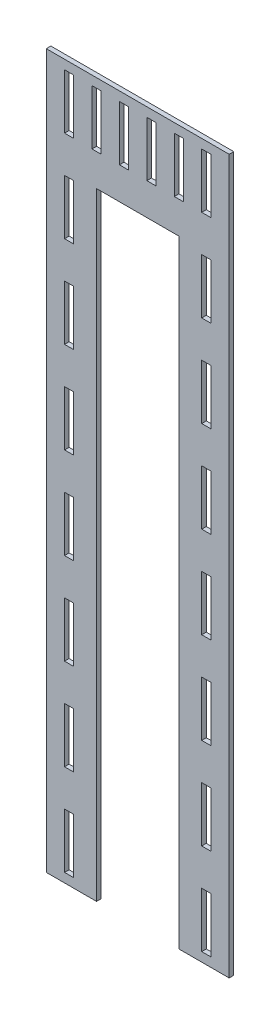
SolidWorks part; units mm, degrees
ref_plane "前视基准面" through (0, 0, 0) normal (0, 0, 1) x (1, 0, 0)
ref_plane "上视基准面" through (0, 0, 0) normal (0, 1, 0) x (1, 0, 0)
ref_plane "右视基准面" through (0, 0, 0) normal (1, 0, 0) x (0, 0, -1)
sketch "草图1" plane through (0, 0, 0) normal (0, 0, 1) x (1, 0, 0)
  line L0 (-4.5, 0) -> (-4.5, 67.5)
  line L1 (-10, 78) -> (10, 78)
  line L2 (-10, 78) -> (-10, 0)
  line L3 (-10, 0) -> (-4.5, 0)
  line L4 (10, 78) -> (10, 0)
  line L5 (-4.5, 67.5) -> (4.5, 67.5)
  line L6 (4.5, 67.5) -> (4.5, 0)
  line L7 (4.5, 0) -> (10, 0)
  dimension "D1" = 20
  dimension "D2" = 78
  dimension "D3" = 10
  dimension "D4" = 9
  dimension "D5" = 4.5
  dimension "D6" = 10.5
extrude "凸台-拉伸1" add sketch "草图1" along normal blind 0.5
sketch "草图3" plane through (0, 0, 0.5) normal (0, 0, 1) x (1, 0, 0)
  line L0 (-10, 78) -> (-10, 0) construction
  line L1 (-8, 77) -> (-7, 77)
  line L2 (-8, 77) -> (-8, 71)
  line L3 (-8, 71) -> (-7, 71)
  line L4 (-7, 77) -> (-7, 71)
  line L5 (10, 78) -> (-10, 78) construction
  line L6 (-5, 77) -> (-5, 71)
  line L7 (-5, 77) -> (-4, 77)
  line L8 (-4, 77) -> (-4, 71)
  line L9 (-5, 71) -> (-4, 71)
  line L10 (-2, 77) -> (-2, 71)
  line L11 (-2, 77) -> (-1, 77)
  line L12 (-1, 77) -> (-1, 71)
  line L13 (-2, 71) -> (-1, 71)
  line L14 (1, 77) -> (1, 71)
  line L15 (1, 77) -> (2, 77)
  line L16 (2, 77) -> (2, 71)
  line L17 (1, 71) -> (2, 71)
  line L18 (4, 77) -> (4, 71)
  line L19 (4, 77) -> (5, 77)
  line L20 (5, 77) -> (5, 71)
  line L21 (4, 71) -> (5, 71)
  line L22 (7, 77) -> (7, 71)
  line L23 (7, 77) -> (8, 77)
  line L24 (8, 77) -> (8, 71)
  line L25 (7, 71) -> (8, 71)
  line L26 (-8, 67) -> (-8, 61)
  line L27 (-8, 67) -> (-7, 67)
  line L28 (-7, 67) -> (-7, 61)
  line L29 (-8, 61) -> (-7, 61)
  line L30 (7, 67) -> (7, 61)
  line L31 (7, 61) -> (8, 61)
  line L32 (8, 67) -> (8, 61)
  line L33 (7, 67) -> (8, 67)
  line L34 (-8, 57) -> (-8, 51)
  line L35 (-8, 57) -> (-7, 57)
  line L36 (-7, 57) -> (-7, 51)
  line L37 (-8, 51) -> (-7, 51)
  line L38 (7, 57) -> (7, 51)
  line L39 (7, 51) -> (8, 51)
  line L40 (8, 57) -> (8, 51)
  line L41 (7, 57) -> (8, 57)
  line L42 (-8, 47) -> (-8, 41)
  line L43 (-8, 47) -> (-7, 47)
  line L44 (-7, 47) -> (-7, 41)
  line L45 (-8, 41) -> (-7, 41)
  line L46 (7, 47) -> (7, 41)
  line L47 (7, 41) -> (8, 41)
  line L48 (8, 47) -> (8, 41)
  line L49 (7, 47) -> (8, 47)
  line L50 (-8, 37) -> (-8, 31)
  line L51 (-8, 37) -> (-7, 37)
  line L52 (-7, 37) -> (-7, 31)
  line L53 (-8, 31) -> (-7, 31)
  line L54 (7, 37) -> (7, 31)
  line L55 (7, 31) -> (8, 31)
  line L56 (8, 37) -> (8, 31)
  line L57 (7, 37) -> (8, 37)
  line L58 (-8, 27) -> (-8, 21)
  line L59 (-8, 27) -> (-7, 27)
  line L60 (-7, 27) -> (-7, 21)
  line L61 (-8, 21) -> (-7, 21)
  line L62 (7, 27) -> (7, 21)
  line L63 (7, 21) -> (8, 21)
  line L64 (8, 27) -> (8, 21)
  line L65 (7, 27) -> (8, 27)
  line L66 (-8, 17) -> (-8, 11)
  line L67 (-8, 17) -> (-7, 17)
  line L68 (-7, 17) -> (-7, 11)
  line L69 (-8, 11) -> (-7, 11)
  line L70 (7, 17) -> (7, 11)
  line L71 (7, 11) -> (8, 11)
  line L72 (8, 17) -> (8, 11)
  line L73 (7, 17) -> (8, 17)
  line L74 (-8, 7) -> (-8, 1)
  line L75 (-8, 7) -> (-7, 7)
  line L76 (-7, 7) -> (-7, 1)
  line L77 (-8, 1) -> (-7, 1)
  line L78 (7, 7) -> (7, 1)
  line L79 (7, 1) -> (8, 1)
  line L80 (8, 7) -> (8, 1)
  line L81 (7, 7) -> (8, 7)
  dimension "D1" = 1
  dimension "D2" = 6
  dimension "D3" = 2
  dimension "D4" = 1
  dimension "D5" = 6
  dimension "D6" = 8
extrude "切除-拉伸1" cut sketch "草图3" against normal blind 0.5
